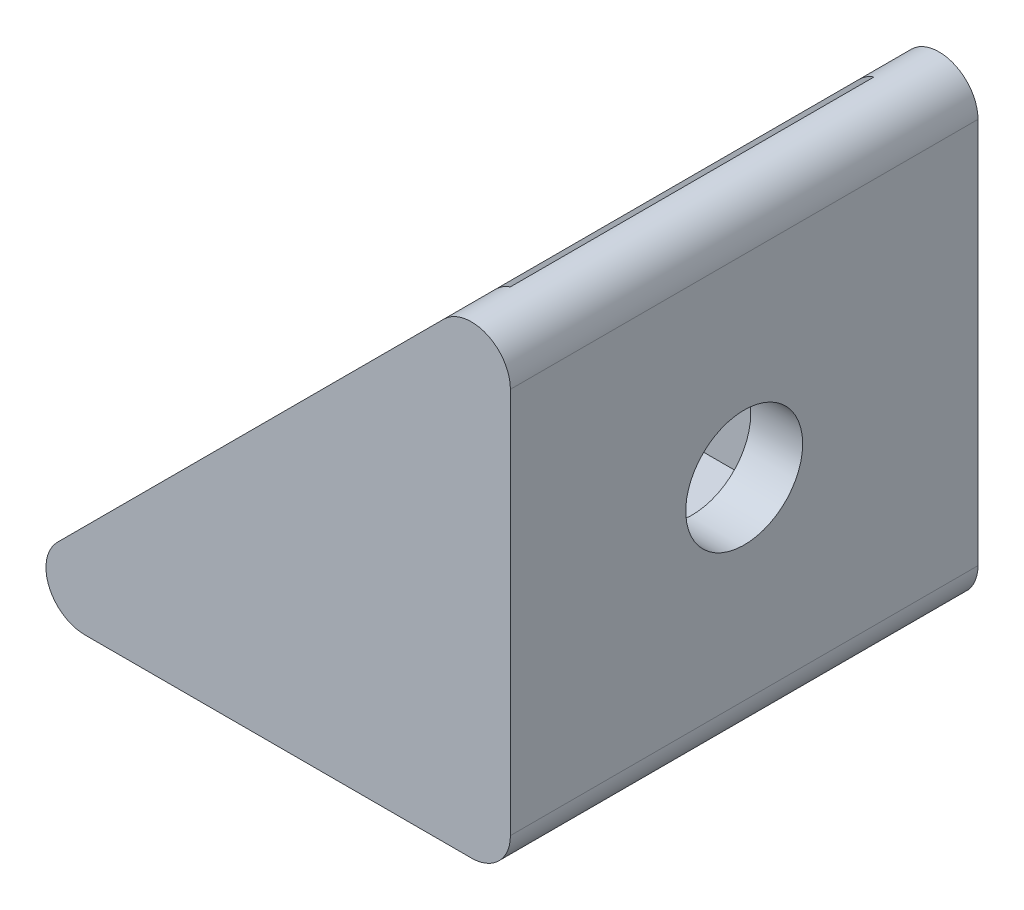
SolidWorks part; units mm, degrees
ref_plane "Plan de face" through (0, 0, 0) normal (0, 0, 1) x (1, 0, 0)
ref_plane "Plan de dessus" through (0, 0, 0) normal (0, 1, 0) x (1, 0, 0)
ref_plane "Plan de droite" through (0, 0, 0) normal (1, 0, 0) x (0, 0, -1)
sketch "Esquisse1" plane through (0, 0, 0) normal (0, 0, 1) x (1, 0, 0)
  line L0 (0, 1.5) -> (0, 16.3787)
  line L1 (-2.5607, 17.4393) -> (-17.4393, 2.5607)
  line L2 (-16.3787, 0) -> (-1.5, 0)
  arc A0 (0, 16.3787) -> (-2.5607, 17.4393) centre (-1.5, 16.3787) ccw
  arc A1 (0, 1.5) -> (-1.5, 0) centre (-1.5, 1.5) cw
  arc A2 (-17.4393, 2.5607) -> (-16.3787, 0) centre (-16.3787, 1.5) ccw
  point P9 (0, 20)
  point P12 (0, 0)
  dimension "D2" = 1.5
  dimension "D1" = 20
extrude "Boss.-Extru.1" add sketch "Esquisse1" along normal blind 18
sketch "Esquisse2" plane through (0, 0, 0) normal (0, -1, 0) x (1, 0, 0)
  line L0 (-16.3787, 0) -> (-1.5, 0) construction
  line L1 (-19.2213, 2) -> (-2, 2)
  line L2 (-19.2213, 2) -> (-19.2213, 16)
  line L3 (-19.2213, 16) -> (-2, 16)
  line L4 (-2, 2) -> (-2, 16)
  line L5 (-16.3787, 18) -> (-1.5, 18) construction
  line L6 (0, 18) -> (0, 0) construction
  dimension "D1" = 2
  dimension "D2" = 2
  dimension "D3" = 2
extrude "Enlèv. mat.-Extru.1" cut sketch "Esquisse2" against normal through all from offset 2 offset against normal yes
hole_wizard "Dégagement M41" positions "Esquisse3" profile "Esquisse4" hole size "M4" standard "ISO" end condition through all
sketch "Esquisse3" plane through (0, 0, 0) normal (1, 0, 0) x (0, 0, -1)
  line L0 (0, 8.9393) -> (-18, 8.9393) construction
  line L1 (0, 1.5) -> (0, 16.3787) construction
  line L2 (-18, 1.5) -> (-18, 16.3787) construction
  point P0 (-9, 8.9393)
sketch "Esquisse4" plane through (0, 8.9393, 9) normal (0, 1, 0) x (0, 0, -1)
  line L0 (0, 0) -> (0, 17.8787)
  line L1 (0, 17.8787) -> (2.25, 17.8787)
  line L2 (2.25, 17.8787) -> (2.25, 0)
  line L5 (2.25, 0) -> (0, 0)
  line L11 (0, -6.35) -> (0, 107.95) construction
  dimension "Diamètre du perçage jusqu'au prochain" = 4.5
  dimension "Profondeur du perçage jusqu'au prochain" = 17.8787
hole_wizard "Dégagement M42" positions "Esquisse5" profile "Esquisse6" hole size "M4" standard "ISO" end condition through all
sketch "Esquisse5" plane through (0, 0, 0) normal (0, -1, 0) x (-1, 0, 0)
  line L0 (8.9393, 0) -> (8.9393, -18) construction
  line L1 (16.3787, 0) -> (1.5, 0) construction
  line L2 (16.3787, -18) -> (1.5, -18) construction
  point P0 (8.9393, -9)
sketch "Esquisse6" plane through (-8.9393, 0, 9) normal (1, 0, 0) x (0, 0, -1)
  line L0 (0, 0) -> (0, 17.8787)
  line L1 (0, 17.8787) -> (2.25, 17.8787)
  line L2 (2.25, 17.8787) -> (2.25, 0)
  line L5 (2.25, 0) -> (0, 0)
  line L11 (0, -6.35) -> (0, 107.95) construction
  dimension "Diamètre du perçage jusqu'au prochain" = 4.5
  dimension "Profondeur du perçage jusqu'au prochain" = 17.8787
